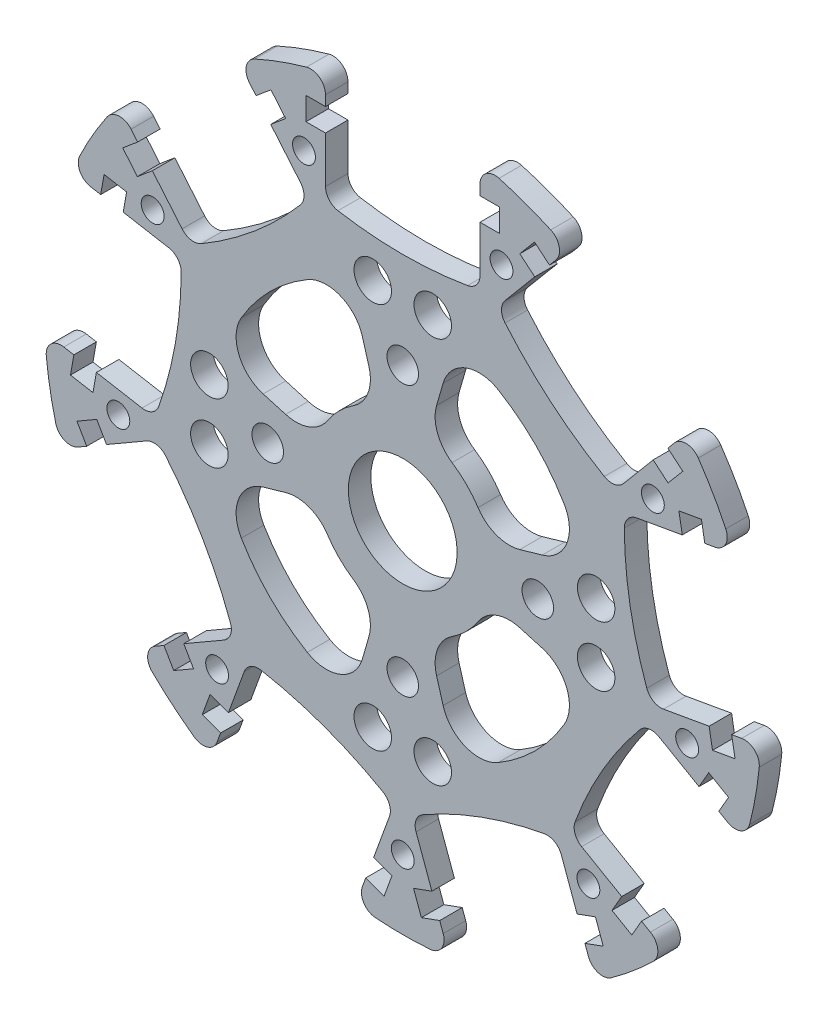
SolidWorks part; units mm, degrees
material "6061 合金"
ref_plane "正面" through (0, 0, 0) normal (0, 0, 1) x (1, 0, 0)
ref_plane "平面" through (0, 0, 0) normal (0, 1, 0) x (1, 0, 0)
ref_plane "右側面" through (0, 0, 0) normal (1, 0, 0) x (0, 0, -1)
sketch "ｽｹｯﾁ1" plane through (0, 0, 0) normal (0, 0, 1) x (1, 0, 0)
  circle A0 centre (0, 0) radius 47.75
  dimension "D1" = 95.5
extrude "ﾎﾞｽ - 押し出し1" add sketch "ｽｹｯﾁ1" along normal blind 3
sketch "ｽｹｯﾁ2" plane through (0, 0, 3) normal (0, 0, 1) x (1, 0, 0)
  line L0 (-10.3, 46.6259) -> (-10.3, 42.705)
  line L1 (10.3, 46.6259) -> (10.3, 42.705)
  line L2 (0, 47.75) -> (0, -47.75) construction
  line L3 (-10.3, 39.655) -> (-10.3, 31.8257)
  line L4 (12.9, 39.655) -> (10.3, 39.655)
  line L5 (12.9, 39.655) -> (12.9, 42.705)
  line L6 (12.9, 42.705) -> (10.3, 42.705)
  line L7 (-12.9, 39.655) -> (-12.9, 42.705)
  line L8 (12.9, 39.655) -> (-12.9, 42.705) construction
  line L9 (12.9, 42.705) -> (-12.9, 39.655) construction
  line L10 (-10.3, 39.655) -> (-12.9, 39.655)
  line L11 (-10.3, 42.705) -> (-12.9, 42.705)
  line L12 (10.3, 39.655) -> (10.3, 31.8257)
  line L13 (0, 30.78) -> (0, 41.18) construction
  line L14 (17.5995, 36.9982) -> (12.5669, 31.0006)
  line L15 (17.5995, 36.9982) -> (15.6078, 38.6695)
  line L16 (15.6078, 38.6695) -> (17.5683, 41.0059)
  line L17 (19.56, 39.3346) -> (17.5683, 41.0059)
  line L18 (22.0803, 42.3382) -> (19.56, 39.3346)
  line L19 (37.8608, 29.0968) -> (35.3405, 26.0932)
  line L20 (37.3322, 24.422) -> (35.3405, 26.0932)
  line L21 (35.3717, 22.0855) -> (37.3322, 24.422)
  line L22 (35.3717, 22.0855) -> (33.38, 23.7568)
  line L23 (33.38, 23.7568) -> (28.3474, 17.7592)
  line L24 (37.264, 17.0295) -> (29.5536, 15.67)
  line L25 (37.264, 17.0295) -> (36.8125, 19.59)
  line L26 (36.8125, 19.59) -> (39.8162, 20.1197)
  line L27 (40.2676, 17.5592) -> (39.8162, 20.1197)
  line L28 (44.1289, 18.24) -> (40.2676, 17.5592)
  line L29 (47.7061, -2.047) -> (43.8448, -2.7279)
  line L30 (44.2963, -5.2884) -> (43.8448, -2.7279)
  line L31 (41.2926, -5.818) -> (44.2963, -5.2884)
  line L32 (41.2926, -5.818) -> (40.8411, -3.2575)
  line L33 (40.8411, -3.2575) -> (33.1308, -4.617)
  line L34 (39.4922, -10.9074) -> (32.7119, -6.9928)
  line L35 (39.4922, -10.9074) -> (40.7922, -8.6558)
  line L36 (40.7922, -8.6558) -> (43.4336, -10.1808)
  line L37 (42.1336, -12.4324) -> (43.4336, -10.1808)
  line L38 (45.5292, -14.3929) -> (42.1336, -12.4324)
  line L39 (35.2292, -32.233) -> (31.8336, -30.2726)
  line L40 (30.5336, -32.5242) -> (31.8336, -30.2726)
  line L41 (27.8922, -30.9992) -> (30.5336, -32.5242)
  line L42 (27.8922, -30.9992) -> (29.1922, -28.7476)
  line L43 (29.1922, -28.7476) -> (22.4119, -24.8329)
  line L44 (23.2416, -33.7407) -> (20.5639, -26.3836)
  line L45 (23.2416, -33.7407) -> (25.6848, -32.8515)
  line L46 (25.6848, -32.8515) -> (26.728, -35.7175)
  line L47 (24.2848, -36.6068) -> (26.728, -35.7175)
  line L48 (25.6258, -40.2912) -> (24.2848, -36.6068)
  line L49 (6.2682, -47.3368) -> (4.9271, -43.6524)
  line L50 (2.4839, -44.5416) -> (4.9271, -43.6524)
  line L51 (1.4408, -41.6756) -> (2.4839, -44.5416)
  line L52 (1.4408, -41.6756) -> (3.884, -40.7863)
  line L53 (3.884, -40.7863) -> (1.2062, -33.4292)
  line L54 (-3.884, -40.7863) -> (-1.2062, -33.4292)
  line L55 (-3.884, -40.7863) -> (-1.4408, -41.6756)
  line L56 (-1.4408, -41.6756) -> (-2.4839, -44.5416)
  line L57 (-4.9271, -43.6524) -> (-2.4839, -44.5416)
  line L58 (-6.2682, -47.3368) -> (-4.9271, -43.6524)
  line L59 (-25.6258, -40.2912) -> (-24.2848, -36.6068)
  line L60 (-26.728, -35.7175) -> (-24.2848, -36.6068)
  line L61 (-25.6848, -32.8515) -> (-26.728, -35.7175)
  line L62 (-25.6848, -32.8515) -> (-23.2416, -33.7407)
  line L63 (-23.2416, -33.7407) -> (-20.5639, -26.3836)
  line L64 (-29.1922, -28.7476) -> (-22.4119, -24.8329)
  line L65 (-29.1922, -28.7476) -> (-27.8922, -30.9992)
  line L66 (-27.8922, -30.9992) -> (-30.5336, -32.5242)
  line L67 (-31.8336, -30.2726) -> (-30.5336, -32.5242)
  line L68 (-35.2292, -32.233) -> (-31.8336, -30.2726)
  line L69 (-45.5292, -14.3929) -> (-42.1336, -12.4324)
  line L70 (-43.4336, -10.1808) -> (-42.1336, -12.4324)
  line L71 (-40.7922, -8.6558) -> (-43.4336, -10.1808)
  line L72 (-40.7922, -8.6558) -> (-39.4922, -10.9074)
  line L73 (-39.4922, -10.9074) -> (-32.7119, -6.9928)
  line L74 (-40.8411, -3.2575) -> (-33.1308, -4.617)
  line L75 (-40.8411, -3.2575) -> (-41.2926, -5.818)
  line L76 (-41.2926, -5.818) -> (-44.2963, -5.2884)
  line L77 (-43.8448, -2.7279) -> (-44.2963, -5.2884)
  line L78 (-47.7061, -2.047) -> (-43.8448, -2.7279)
  line L79 (-44.1289, 18.24) -> (-40.2676, 17.5592)
  line L80 (-39.8162, 20.1197) -> (-40.2676, 17.5592)
  line L81 (-36.8125, 19.59) -> (-39.8162, 20.1197)
  line L82 (-36.8125, 19.59) -> (-37.264, 17.0295)
  line L83 (-37.264, 17.0295) -> (-29.5536, 15.67)
  line L84 (-33.38, 23.7568) -> (-28.3474, 17.7592)
  line L85 (-33.38, 23.7568) -> (-35.3717, 22.0855)
  line L86 (-35.3717, 22.0855) -> (-37.3322, 24.422)
  line L87 (-35.3405, 26.0932) -> (-37.3322, 24.422)
  line L88 (-37.8608, 29.0968) -> (-35.3405, 26.0932)
  line L89 (-22.0803, 42.3382) -> (-19.56, 39.3346)
  line L90 (-17.5683, 41.0059) -> (-19.56, 39.3346)
  line L91 (-15.6078, 38.6695) -> (-17.5683, 41.0059)
  line L92 (-15.6078, 38.6695) -> (-17.5995, 36.9982)
  line L93 (-17.5995, 36.9982) -> (-12.5669, 31.0006)
  circle A0 centre (0, 0) radius 47.75 construction
  arc A1 (-10.3, 46.6259) -> (10.3, 46.6259) centre (0, 0) cw
  arc A2 (-10.3, 31.8257) -> (10.3, 31.8257) centre (0, 82.03) ccw
  arc A3 (12.5669, 31.0006) -> (28.3474, 17.7592) centre (52.7279, 62.8386) ccw
  arc A4 (22.0803, 42.3382) -> (37.8608, 29.0968) centre (0, 0) cw
  arc A5 (29.5536, 15.67) -> (33.1308, -4.617) centre (80.7838, 14.2444) ccw
  arc A6 (44.1289, 18.24) -> (47.7061, -2.047) centre (0, 0) cw
  arc A7 (32.7119, -6.9928) -> (22.4119, -24.8329) centre (71.0401, -41.015) ccw
  arc A8 (45.5292, -14.3929) -> (35.2292, -32.233) centre (0, 0) cw
  arc A9 (20.5639, -26.3836) -> (1.2062, -33.4292) centre (28.0559, -77.083) ccw
  arc A10 (25.6258, -40.2912) -> (6.2682, -47.3368) centre (0, 0) cw
  arc A11 (-1.2062, -33.4292) -> (-20.5639, -26.3836) centre (-28.0559, -77.083) ccw
  arc A12 (-6.2682, -47.3368) -> (-25.6258, -40.2912) centre (0, 0) cw
  arc A13 (-22.4119, -24.8329) -> (-32.7119, -6.9928) centre (-71.0401, -41.015) ccw
  arc A14 (-35.2292, -32.233) -> (-45.5292, -14.3929) centre (0, 0) cw
  arc A15 (-33.1308, -4.617) -> (-29.5536, 15.67) centre (-80.7838, 14.2444) ccw
  arc A16 (-47.7061, -2.047) -> (-44.1289, 18.24) centre (0, 0) cw
  arc A17 (-28.3474, 17.7592) -> (-12.5669, 31.0006) centre (-52.7279, 62.8386) ccw
  arc A18 (-37.8608, 29.0968) -> (-22.0803, 42.3382) centre (0, 0) cw
  point P11 (0, 41.18)
  point P139 (0, 0)
  dimension "D2" = 20.6
  dimension "D7" = 51.25
  dimension "D1" = 41.18
  dimension "D3" = 10.3
  dimension "D4" = 3.05
  dimension "D5" = 25.8
  dimension "D6" = 10.4
  dimension "D8" = 9
extrude "ｶｯﾄ - 押し出し1" cut sketch "ｽｹｯﾁ2" against normal through all
fillet "ﾌｨﾚｯﾄ2" radius 2 36 edges at (-12.5669, 31.0006, 1.5) (-28.3474, 17.7592, 1.5) (-29.5536, 15.67, 1.5) (-33.1308, -4.617, 1.5) (-32.7119, -6.9928, 1.5) (-22.4119, -24.8329, 1.5) (-20.5639, -26.3836, 1.5) (-1.2062, -33.4292, 1.5) (1.2062, -33.4292, 1.5) (20.5639, -26.3836, 1.5) (32.7119, -6.9928, 1.5) (22.4119, -24.8329, 1.5) (33.1308, -4.617, 1.5) (29.5536, 15.67, 1.5) (28.3474, 17.7592, 1.5) (12.5669, 31.0006, 1.5) (10.3, 31.8257, 1.5) (-10.3, 31.8257, 1.5) (35.2292, -32.233, 1.5) (25.6258, -40.2912, 1.5) (6.2682, -47.3368, 1.5) (-6.2682, -47.3368, 1.5) (-25.6258, -40.2912, 1.5) (-35.2292, -32.233, 1.5) (-45.5292, -14.3929, 1.5) (-47.7061, -2.047, 1.5) (-44.1289, 18.24, 1.5) (-37.8608, 29.0968, 1.5) (-22.0803, 42.3382, 1.5) (-10.3, 46.6259, 1.5) (22.0803, 42.3382, 1.5) (10.3, 46.6259, 1.5) (37.8608, 29.0968, 1.5) (44.1289, 18.24, 1.5) (47.7061, -2.047, 1.5) (45.5292, -14.3929, 1.5)
sketch "ｽｹｯﾁ3" plane through (0, 0, 3) normal (0, 0, 1) x (1, 0, 0)
  line L0 (0, 0) -> (0, -38.5) construction
  line L1 (0, 0) -> (-24.7473, -29.4927) construction
  line L2 (0, 0) -> (-37.9151, -6.6855) construction
  line L3 (0, 0) -> (-33.342, 19.25) construction
  line L4 (0, 0) -> (-13.1678, 36.1782) construction
  line L5 (0, 0) -> (13.1678, 36.1782) construction
  line L6 (0, 0) -> (33.342, 19.25) construction
  line L7 (0, 0) -> (37.9151, -6.6855) construction
  line L8 (0, 0) -> (24.7473, -29.4927) construction
  circle A2 centre (0, -38.5) radius 1.525
  circle A3 centre (0, 0) radius 38.5 construction
  circle A4 centre (-24.7473, -29.4927) radius 1.525
  circle A5 centre (0, 0) radius 38.5 construction
  circle A6 centre (-37.9151, -6.6855) radius 1.525
  circle A7 centre (0, 0) radius 38.5 construction
  circle A8 centre (-33.342, 19.25) radius 1.525
  circle A9 centre (0, 0) radius 38.5 construction
  circle A10 centre (-13.1678, 36.1782) radius 1.525
  circle A11 centre (0, 0) radius 38.5 construction
  circle A12 centre (13.1678, 36.1782) radius 1.525
  circle A13 centre (0, 0) radius 38.5 construction
  circle A14 centre (33.342, 19.25) radius 1.525
  circle A15 centre (0, 0) radius 38.5 construction
  circle A16 centre (37.9151, -6.6855) radius 1.525
  circle A17 centre (0, 0) radius 38.5 construction
  circle A18 centre (24.7473, -29.4927) radius 1.525
  circle A19 centre (0, 0) radius 38.5 construction
  point P10 (0, 0)
  point P32 (0, 0)
  dimension "D1" = 3.05
  dimension "D2" = 77
  dimension "D3" = 9
extrude "ｶｯﾄ - 押し出し2" cut sketch "ｽｹｯﾁ3" against normal through all
sketch "ｽｹｯﾁ4" plane through (0, 0, 0) normal (0, 0, -1) x (-1, 0, 0)
  line L0 (0, -48.3338) -> (0, 30.1962) construction
  circle A0 centre (18, 0) radius 2.1
  circle A1 centre (0, -18) radius 2.1
  circle A2 centre (0, 18) radius 2.1
  circle A3 centre (0, 0) radius 18 construction
  circle A4 centre (0, 0) radius 7.25
  circle A5 centre (-18, 0) radius 2.1
  point P11 (0, 0)
  dimension "D2" = 4.2
  dimension "D4" = 14.5
  dimension "D1" = 18
  dimension "D3" = 4
extrude "ｶｯﾄ - 押し出し3" cut sketch "ｽｹｯﾁ4" against normal through all
sketch "ｽｹｯﾁ7" plane through (0, 0, 0) normal (0, 0, -1) x (-1, 0, 0)
  line L0 (0, 0) -> (-31.5531, 0) construction
  line L1 (0, 0) -> (-30.3124, 5.3449) construction
  line L3 (0, 0) -> (-5.4791, 31.0737) construction
  line L9 (0, 0) -> (0, 18) construction
  line L10 (-3.3333, 11.5277) -> (-6.9444, 24.0161)
  line L11 (0, 18) -> (-4.8032, 16.6111) construction
  line L12 (-11.5277, 3.3333) -> (-24.0161, 6.9444)
  line L13 (-18, 0) -> (-16.6111, 4.8032) construction
  arc A1 (-32.5341, -3.0337) -> (-29.5345, 13.978) centre (-80.7838, 14.2444) ccw construction
  arc A4 (-8.6371, 31.513) -> (8.6371, 31.513) centre (0, 82.03) ccw construction
  arc A7 (-24.0161, 6.9444) -> (-6.9444, 24.0161) centre (0, 0) cw
  arc A8 (-11.5277, 3.3333) -> (-3.3333, 11.5277) centre (0, 0) cw
  dimension "D1" = 5
  dimension "D3" = 5
  dimension "D4" = 25
  dimension "D5" = 12
  dimension "D2" = 70
  dimension "D6" = 16.128
  dimension "D7" = 16.128
extrude "ｶｯﾄ - 押し出し4" cut sketch "ｽｹｯﾁ7" against normal through all
fillet "ﾌｨﾚｯﾄ3" radius 5 4 edges at (11.5277, 3.3333, 1.5) (24.0161, 6.9444, 1.5) (6.9444, 24.0161, 1.5) (3.3333, 11.5277, 1.5)
pattern_circular "円形ﾊﾟﾀｰﾝ1" count 4 over 360 about axis through (0, 0, 0) along (0, 0, 1) of "ﾌｨﾚｯﾄ3", "ｶｯﾄ - 押し出し4"
sketch "ｽｹｯﾁ8" plane through (0, 0, 0) normal (0, 0, -1) x (-1, 0, 0)
  line L0 (0, -47.75) -> (0, 30.78) construction
  line L1 (-9.9226, 25.78) -> (9.5126, 25.78) construction
  arc A0 (-3.6667, -47.609) -> (3.6667, -47.609) centre (0, 0) ccw construction
  arc A1 (-8.6371, 31.513) -> (8.6371, 31.513) centre (0, 82.03) ccw construction
  circle A2 centre (-4, 25.78) radius 2.5
  circle A3 centre (4, 25.78) radius 2.5
  dimension "D2" = 5
  dimension "D3" = 5
  dimension "D4" = 4
  dimension "D5" = 8
  dimension "D1" = 5
extrude "ｶｯﾄ - 押し出し5" cut sketch "ｽｹｯﾁ8" against normal through all
pattern_circular "円形ﾊﾟﾀｰﾝ2" count 4 over 360 about axis through (0, 0, 0) along (0, 0, 1) of "ｶｯﾄ - 押し出し5"
